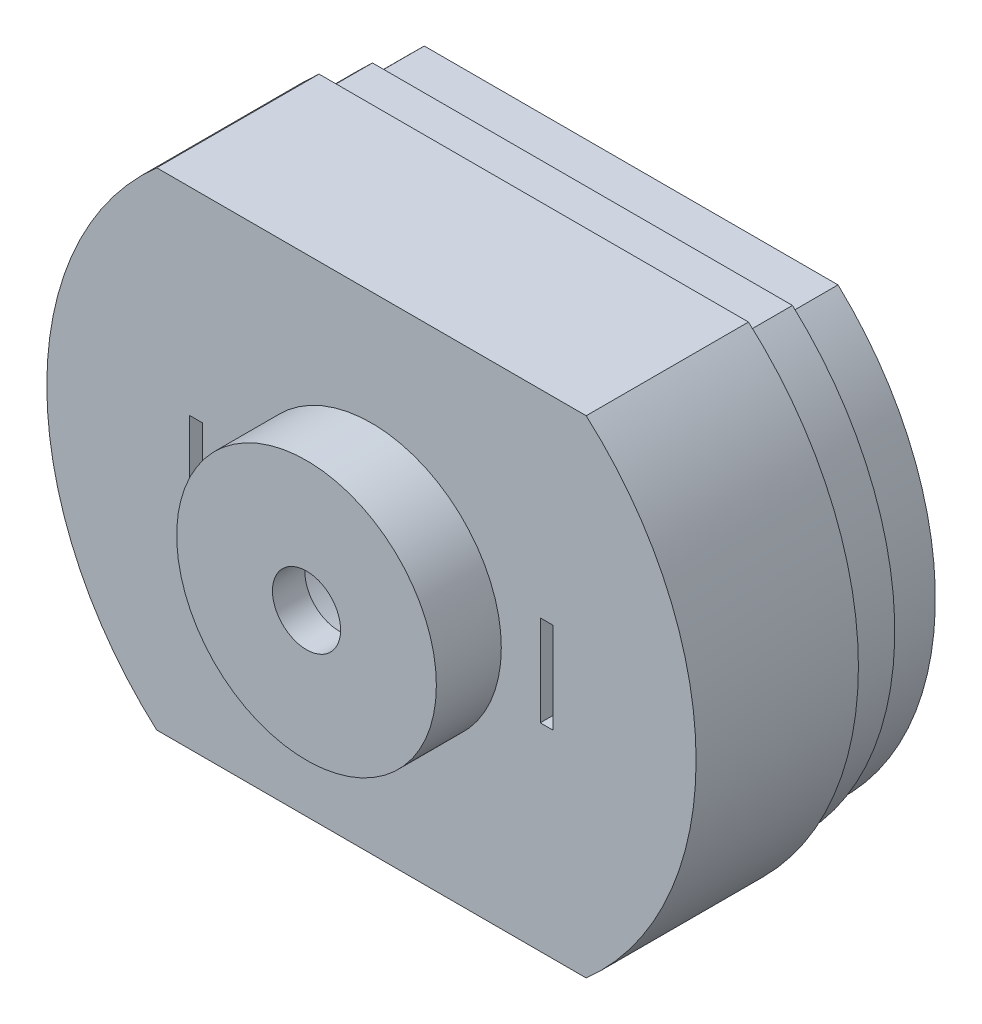
SolidWorks part; units mm, degrees
ref_plane "Front Plane" through (0, 0, 0) normal (0, 0, 1) x (1, 0, 0)
ref_plane "Top Plane" through (0, 0, 0) normal (0, 1, 0) x (1, 0, 0)
ref_plane "Right Plane" through (0, 0, 0) normal (1, 0, 0) x (0, 0, -1)
sketch "Sketch1" plane through (0, 0, 0) normal (0, 0, 1) x (1, 0, 0)
  line L0 (0, 0) -> (0, 6375.3) construction
  line L1 (-6.615, 7.5) -> (6.615, 7.5)
  line L2 (-6.615, 7.5) -> (-6.615, -7.5) construction
  line L3 (-6.615, -7.5) -> (6.615, -7.5)
  line L4 (6.615, 7.5) -> (6.615, -7.5) construction
  line L5 (-6.615, 7.5) -> (6.615, -7.5) construction
  line L6 (-6.615, -7.5) -> (6.615, 7.5) construction
  arc A0 (-6.615, 7.5) -> (-6.615, -7.5) centre (-0.0006, 0) ccw
  arc A1 (6.615, 7.5) -> (6.615, -7.5) centre (0.0006, 0) cw
  point P0 (0, 0)
  dimension "D3" = 10
  dimension "D1" = 13.23
  dimension "D2" = 15
extrude "Boss-Extrude1" add sketch "Sketch1" along normal blind 5
sketch "Sketch2" plane through (0, 0, 5) normal (0, 0, 1) x (1, 0, 0)
  circle A0 centre (0, 0) radius 4
  dimension "D1" = 8
extrude "Boss-Extrude2" add sketch "Sketch2" along normal blind 2
sketch "Sketch3" plane through (0, 0, 0) normal (0, 0, -1) x (-1, 0, 0)
  line L0 (6.4698, 7.12) -> (-6.4698, 7.12)
  line L1 (-6.4698, -7.12) -> (6.4698, -7.12)
  line L2 (-6.615, -7.5) -> (6.615, -7.5)
  line L3 (6.615, 7.5) -> (-6.615, 7.5)
  line L4 (-6.615, -7.5) -> (6.615, -7.5)
  line L5 (6.615, 7.5) -> (-6.615, 7.5)
  arc A0 (-6.4698, 7.12) -> (-6.4698, -7.12) centre (-0.0006, 0) ccw
  arc A1 (6.4698, -7.12) -> (6.4698, 7.12) centre (0.0006, 0) ccw
  arc A2 (-6.615, 7.5) -> (-6.615, -7.5) centre (-0.0006, 0) ccw
  arc A3 (6.615, -7.5) -> (6.615, 7.5) centre (0.0006, 0) ccw
  arc A4 (-6.615, 7.5) -> (-6.615, -7.5) centre (-0.0006, 0) ccw
  arc A5 (6.615, -7.5) -> (6.615, 7.5) centre (0.0006, 0) ccw
  dimension "D1" = 0
  dimension "D2" = 0.38
extrude "Boss-Extrude3" add sketch "Sketch3" along normal blind 1.5 contours L1 A1 L0 A0
sketch "Sketch4" plane through (0, 0, -1.5) normal (0, 0, -1) x (-1, 0, 0)
  line L0 (-6.3724, -6.87) -> (6.3724, -6.87)
  line L1 (6.3724, 6.87) -> (-6.3724, 6.87)
  line L2 (-6.4698, -7.12) -> (6.4698, -7.12)
  line L3 (6.4698, 7.12) -> (-6.4698, 7.12)
  line L4 (-6.4698, -7.12) -> (6.4698, -7.12)
  line L5 (6.4698, 7.12) -> (-6.4698, 7.12)
  arc A0 (-6.3724, 6.87) -> (-6.3724, -6.87) centre (-0.0006, 0) ccw
  arc A1 (6.3724, -6.87) -> (6.3724, 6.87) centre (0.0006, 0) ccw
  arc A2 (6.4698, -7.12) -> (6.4698, 7.12) centre (0.0006, 0) ccw
  arc A3 (-6.4698, 7.12) -> (-6.4698, -7.12) centre (-0.0006, 0) ccw
  arc A4 (6.4698, -7.12) -> (6.4698, 7.12) centre (0.0006, 0) ccw
  arc A5 (-6.4698, 7.12) -> (-6.4698, -7.12) centre (-0.0006, 0) ccw
  dimension "D1" = 0
  dimension "D2" = 0.25
extrude "Boss-Extrude4" add sketch "Sketch4" along normal blind 1.5 contours L0 A1 L1 A0
sketch "Sketch5" plane through (0, 0, -3) normal (0, 0, -1) x (-1, 0, 0)
  line L0 (-6.2736, -6.62) -> (6.2736, -6.62)
  line L1 (6.2736, 6.62) -> (-6.2736, 6.62)
  line L2 (-6.3724, -6.87) -> (6.3724, -6.87)
  line L3 (6.3724, 6.87) -> (-6.3724, 6.87)
  line L4 (-6.3724, -6.87) -> (6.3724, -6.87)
  line L5 (6.3724, 6.87) -> (-6.3724, 6.87)
  line L6 (-6.3744, 2) -> (-7.6306, 4.9957)
  line L7 (-6.3744, 2) -> (6.3756, 2)
  line L8 (-6.3744, 2) -> (-6.3744, -2)
  line L9 (-6.3744, -2) -> (6.3756, -2)
  line L10 (6.3756, 2) -> (6.3756, -2)
  line L11 (-6.3744, 2) -> (6.3756, -2) construction
  line L12 (-6.3744, -2) -> (6.3756, 2) construction
  line L13 (6.3756, 2) -> (7.6394, 4.9823)
  line L14 (0.0006, 0) -> (50000.0006, 0) construction
  line L15 (6.3756, -2) -> (7.6394, -4.9823)
  line L16 (-6.3744, -2) -> (-7.6306, -4.9957)
  arc A0 (-6.2736, 6.62) -> (-7.6306, 4.9957) centre (-0.0006, 0) ccw
  arc A1 (6.2736, -6.62) -> (7.6394, -4.9823) centre (0.0006, 0) ccw
  arc A2 (6.3724, -6.87) -> (6.3724, 6.87) centre (0.0006, 0) ccw
  arc A3 (-6.3724, 6.87) -> (-6.3724, -6.87) centre (-0.0006, 0) ccw
  arc A4 (6.3724, -6.87) -> (9.3706, 0) centre (0.0006, 0) ccw construction
  arc A5 (-9.3706, 0) -> (-6.3724, -6.87) centre (-0.0006, 0) ccw construction
  arc A6 (-6.3724, 6.87) -> (-9.3706, 0) centre (-0.0006, 0) ccw construction
  arc A7 (-6.3724, 6.87) -> (-6.3724, -6.87) centre (-0.0006, 0) ccw construction
  arc A8 (-7.6306, 4.9957) -> (-9.1206, 0) centre (-0.0006, 0) ccw construction
  arc A9 (-7.6306, -4.9957) -> (-6.2736, -6.62) centre (-0.0006, 0) ccw
  arc A10 (-6.2736, 6.62) -> (-6.2736, -6.62) centre (-0.0006, 0) ccw construction
  arc A11 (9.3706, 0) -> (6.3724, 6.87) centre (0.0006, 0) ccw construction
  arc A12 (6.3724, -6.87) -> (6.3724, 6.87) centre (0.0006, 0) ccw construction
  arc A13 (9.1206, 0) -> (7.6394, 4.9823) centre (0.0006, 0) ccw construction
  arc A14 (7.6394, 4.9823) -> (6.2736, 6.62) centre (0.0006, 0) ccw
  arc A15 (6.2736, -6.62) -> (6.2736, 6.62) centre (0.0006, 0) ccw construction
  arc A16 (7.6394, -4.9823) -> (9.1206, 0) centre (0.0006, 0) ccw construction
  arc A17 (-9.1206, 0) -> (-7.6306, -4.9957) centre (-0.0006, 0) ccw construction
  dimension "D3" = 4
  dimension "D4" = 12.75
  dimension "D5" = 15.27
  dimension "D6" = 7.64
  dimension "D1" = 0
  dimension "D2" = 0.25
extrude "Cut-Extrude1" cut sketch "Sketch5" against normal blind 6.5 contours L16 A9 L0 A1 L15 L9 | L10 L7 L8 L9 | L13 A14 L1 A0 L6 L7
sketch "Sketch6" plane through (0, 0, 3.5) normal (0, 0, -1) x (-1, 0, 0)
  circle A0 centre (0, 0) radius 3
  dimension "D1" = 6
extrude "Cut-Extrude2" cut sketch "Sketch6" against normal blind 2.5
sketch "Sketch7" plane through (0, 0, 6) normal (0, 0, -1) x (-1, 0, 0)
  circle A0 centre (0, 0) radius 1.05
  dimension "D1" = 2.1
extrude "Cut-Extrude3" cut sketch "Sketch7" against normal blind 2.5
sketch "Sketch8" plane through (0, 0, 3.5) normal (0, 0, -1) x (-1, 0, 0)
  line L0 (0, 0) -> (0, 4.8196) construction
  line L1 (-5.6, 1.4) -> (-5.2, 1.4)
  line L2 (-5.6, 1.4) -> (-5.6, -1.4)
  line L3 (-5.6, -1.4) -> (-5.2, -1.4)
  line L4 (-5.2, 1.4) -> (-5.2, -1.4)
  line L5 (-5.6, 1.4) -> (-5.2, -1.4) construction
  line L6 (-5.6, -1.4) -> (-5.2, 1.4) construction
  line L7 (5.6, -1.4) -> (5.2, 1.4) construction
  line L8 (5.6, 1.4) -> (5.2, -1.4) construction
  line L9 (5.2, 1.4) -> (5.2, -1.4)
  line L10 (5.6, -1.4) -> (5.2, -1.4)
  line L11 (5.6, 1.4) -> (5.6, -1.4)
  line L12 (5.6, 1.4) -> (5.2, 1.4)
  point P0 (-5.4, 0)
  point P12 (5.4, 0)
  dimension "D1" = 0.4
  dimension "D2" = 2.8
  dimension "D3" = 5.2
extrude "Cut-Extrude4" cut sketch "Sketch8" against normal blind 2.5
sketch "Sketch9" plane through (0, 0, 5) normal (0, 0, 1) x (1, 0, 0)
  line L0 (0, 0) -> (0, 5.1537) construction
  line L1 (-12.1106, 1.5) -> (-9.1106, 1.5)
  line L2 (-12.1106, 1.5) -> (-12.1106, -1.5)
  line L3 (-12.1106, -1.5) -> (-9.1106, -1.5)
  line L4 (-9.1106, 1.5) -> (-9.1106, -1.5)
  line L5 (-12.1106, 1.5) -> (-9.1106, -1.5) construction
  line L6 (-12.1106, -1.5) -> (-9.1106, 1.5) construction
  line L7 (12.1106, -1.5) -> (9.1106, 1.5) construction
  line L8 (12.1106, 1.5) -> (9.1106, -1.5) construction
  line L9 (9.1106, 1.5) -> (9.1106, -1.5)
  line L10 (12.1106, -1.5) -> (9.1106, -1.5)
  line L11 (12.1106, 1.5) -> (12.1106, -1.5)
  line L12 (12.1106, 1.5) -> (9.1106, 1.5)
  arc A0 (-9.1106, -1.5) -> (-9.1106, 1.5) centre (-9.1106, 0) ccw
  arc A1 (-6.615, 7.5) -> (-6.615, -7.5) centre (-0.0006, 0) ccw construction
  arc A2 (-9.1106, 1.5) -> (-9.1436, 1.4996) centre (-9.1106, 0) ccw construction
  arc A3 (-9.1893, -1.4979) -> (-9.1886, -1.498) centre (-9.1106, 0) ccw construction
  arc A4 (9.1893, -1.4979) -> (9.1886, -1.498) centre (9.1106, 0) cw construction
  arc A5 (9.1106, 1.5) -> (9.1436, 1.4996) centre (9.1106, 0) cw construction
  arc A6 (9.1106, -1.5) -> (9.1106, 1.5) centre (9.1106, 0) cw
  point P5 (-10.0006, 0)
  point P6 (-10.6106, 0)
  point P24 (10.6106, 0)
  dimension "D1" = 3
  dimension "D2" = 0.89
